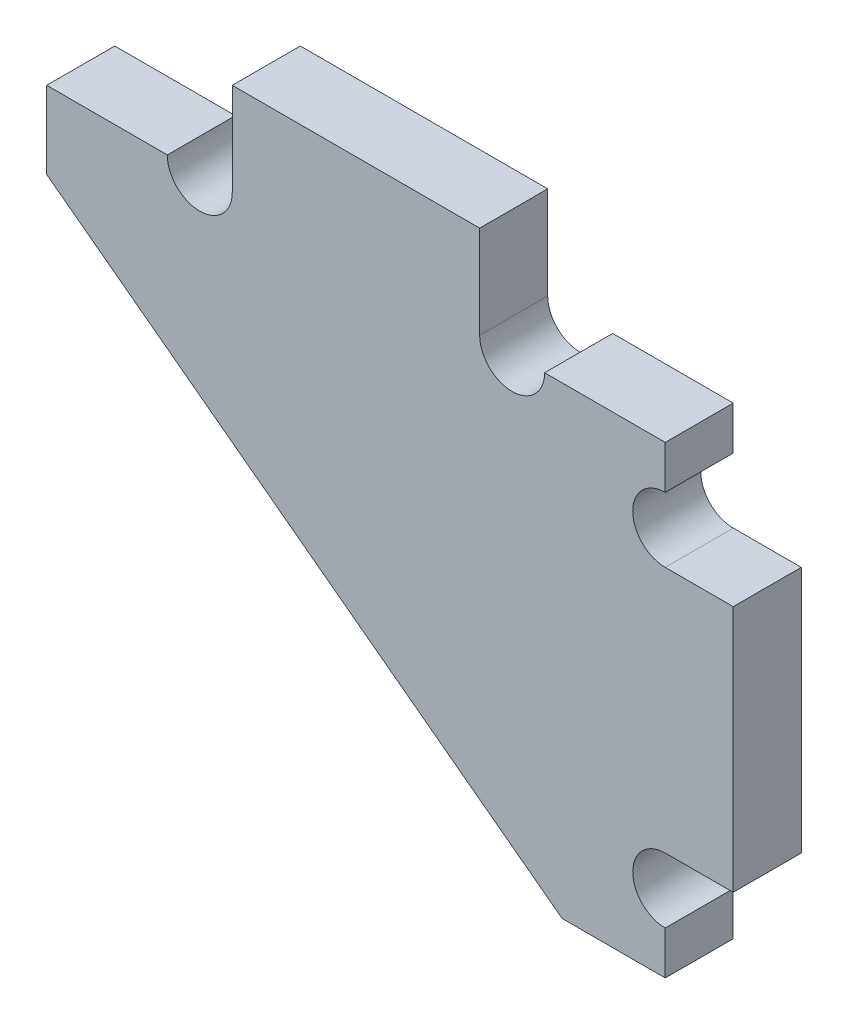
SolidWorks part; units mm, degrees
material "Thornel Mat VMA"
ref_plane "前视基准面" through (0, 0, 0) normal (0, 0, 1) x (1, 0, 0)
ref_plane "上视基准面" through (0, 0, 0) normal (0, 1, 0) x (1, 0, 0)
ref_plane "右视基准面" through (0, 0, 0) normal (1, 0, 0) x (0, 0, -1)
sketch "草图1" plane through (0, 0, 0) normal (0, 0, 1) x (1, 0, 0)
  line L0 (-4, 7.5) -> (-4, 10.5)
  line L1 (10, -7.5) -> (-10, -7.5) construction
  line L2 (10, -7.5) -> (10, -4)
  line L3 (10, 7.5) -> (4, 7.5)
  line L4 (-10, -7.5) -> (-10, 7.5) construction
  line L5 (10, -7.5) -> (-10, 7.5) construction
  line L6 (10, 7.5) -> (-10, -7.5) construction
  line L7 (-4, 10.5) -> (4, 10.5)
  line L8 (4, 10.5) -> (4, 7.5)
  line L9 (0, 10.5) -> (0, 5.6201) construction
  line L10 (10, 4) -> (12.2, 4)
  line L11 (12.2, 4) -> (12.2, -4)
  line L12 (12.2, -4) -> (10, -4)
  line L13 (12.2, 0) -> (6.0465, 0) construction
  line L14 (10, 4) -> (10, 7.5)
  line L15 (-4, 7.5) -> (-10, 7.5)
  line L16 (-10, 5) -> (6.6667, -7.5)
  line L17 (-10, 5) -> (-10, 7.5)
  line L18 (6.6667, -7.5) -> (10, -7.5)
  circle A0 centre (10, 5.05) radius 1.05
  circle A1 centre (10, -5.05) radius 1.05
  circle A2 centre (-5.05, 7.5) radius 1.05
  circle A3 centre (5.05, 7.5) radius 1.05
  point P0 (0, 0)
  dimension "D7" = 2.1
  dimension "D1" = 8
  dimension "D2" = 3
  dimension "D3" = 20
  dimension "D4" = 15
  dimension "D5" = 8
  dimension "D6" = 2.2
  dimension "D8" = 2
extrude "凸台-拉伸1" add sketch "草图1" along normal blind 2.2 contours A3 L8 L7 L0 A2 L15 L17 L16 L18 L2 A1 L12 L11 L10 A0 L14 L3
